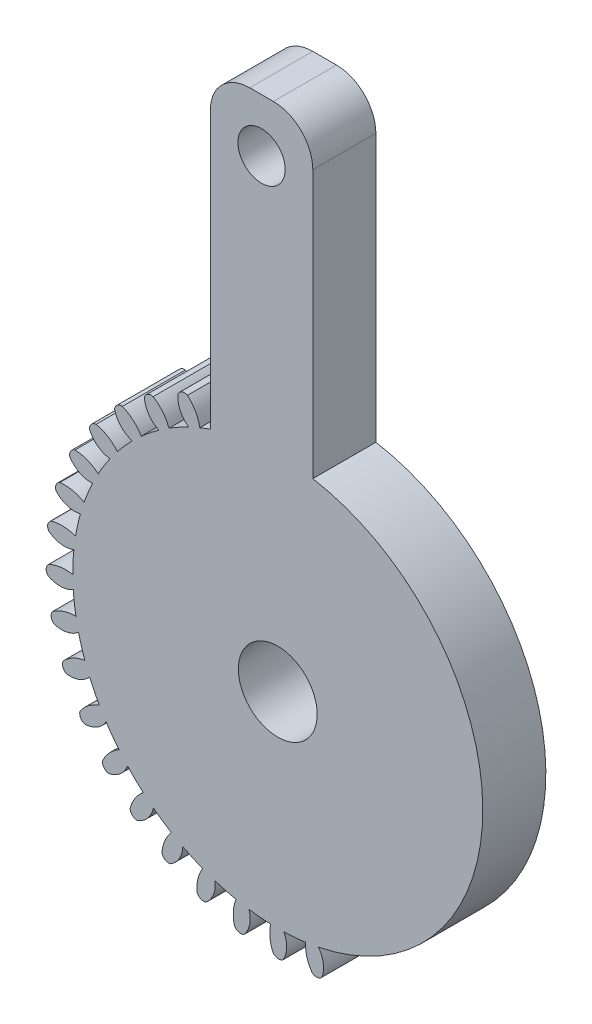
SolidWorks part; units mm, degrees
ref_plane "Front Plane" through (0, 0, 0) normal (0, 0, 1) x (1, 0, 0)
ref_plane "Top Plane" through (0, 0, 0) normal (0, 1, 0) x (1, 0, 0)
ref_plane "Right Plane" through (0, 0, 0) normal (1, 0, 0) x (0, 0, -1)
sketch "Sketch1" plane through (0, 0, 0) normal (0, 0, 1) x (1, 0, 0)
  circle A0 centre (0, 0) radius 13
extrude "Boss-Extrude1" add sketch "Sketch1" along normal blind 4
sketch "Sketch2" plane through (0, 0, 4) normal (0, 0, 1) x (1, 0, 0)
  line L0 (-1.4428, 12.9197) -> (-0.6734, 12.9825)
  arc A0 (-0.6734, 12.9825) -> (-0.9461, 14.5534) centre (-3.0521, 13.3787) ccw
  circle A1 centre (0, 0) radius 13 construction
  arc A2 (-0.9461, 14.5534) -> (-1.5815, 14.5534) centre (-1.2638, 14.2357) ccw
  arc A3 (-1.5815, 14.5534) -> (-1.4428, 12.9197) centre (-0.1322, 13.8537) ccw
extrude "Boss-Extrude2" add sketch "Sketch2" against normal blind 4
pattern_circular "CirPattern1" count 37 over 360 about axis through (-0.0036, 0.0409, 0) along (0, 0, 1) of "Boss-Extrude2"
sketch "Sketch3" plane through (0, 0, 4) normal (0, 0, 1) x (1, 0, 0)
  arc A0 (2.5802, -12.7414) -> (2.9293, 12.6657) centre (0, 0) ccw
  arc A1 (3.0764, -15.1916) -> (3.4926, 15.1014) centre (0, 0) ccw
  arc A2 (2.5802, -12.7414) -> (3.0764, -15.1916) centre (1.6032, -14.2146) cw
  arc A3 (3.4926, 15.1014) -> (2.9293, 12.6657) centre (4.4288, 13.6019) ccw
  dimension "D1" = 2.5
extrude "Cut-Extrude1" cut sketch "Sketch3" against normal blind 6
sketch "Sketch5" plane through (0, 0, 4) normal (0, 0, 1) x (1, 0, 0)
  line L1 (-4.2795, 12.2754) -> (2.2205, 12.2754)
  line L2 (-4.2795, 12.2754) -> (-4.2795, 32.2754)
  line L3 (-4.2795, 32.2754) -> (2.2205, 32.2754)
  line L4 (2.2205, 12.2754) -> (2.2205, 32.2754)
  arc A0 (-3.5992, 12.4918) -> (-4.9469, 12.022) centre (0, 0) ccw construction
  dimension "D1" = 20
  dimension "D2" = 6.5
extrude "Boss-Extrude3" add sketch "Sketch5" against normal blind 4
fillet "Fillet1" radius 2.5 2 edges at (2.2205, 32.2754, 2) (-4.2795, 32.2754, 2)
sketch "Sketch6" plane through (0, 0, 4) normal (0, 0, 1) x (1, 0, 0)
  circle A0 centre (0, 0) radius 2.5
  dimension "D1" = 5
extrude "Cut-Extrude2" cut sketch "Sketch6" against normal through all
sketch "Sketch7" plane through (0, 0, 4) normal (0, 0, 1) x (1, 0, 0)
  circle A0 centre (-1.0295, 28.9069) radius 1.5
  dimension "D1" = 3
extrude "Cut-Extrude3" cut sketch "Sketch7" against normal through all
